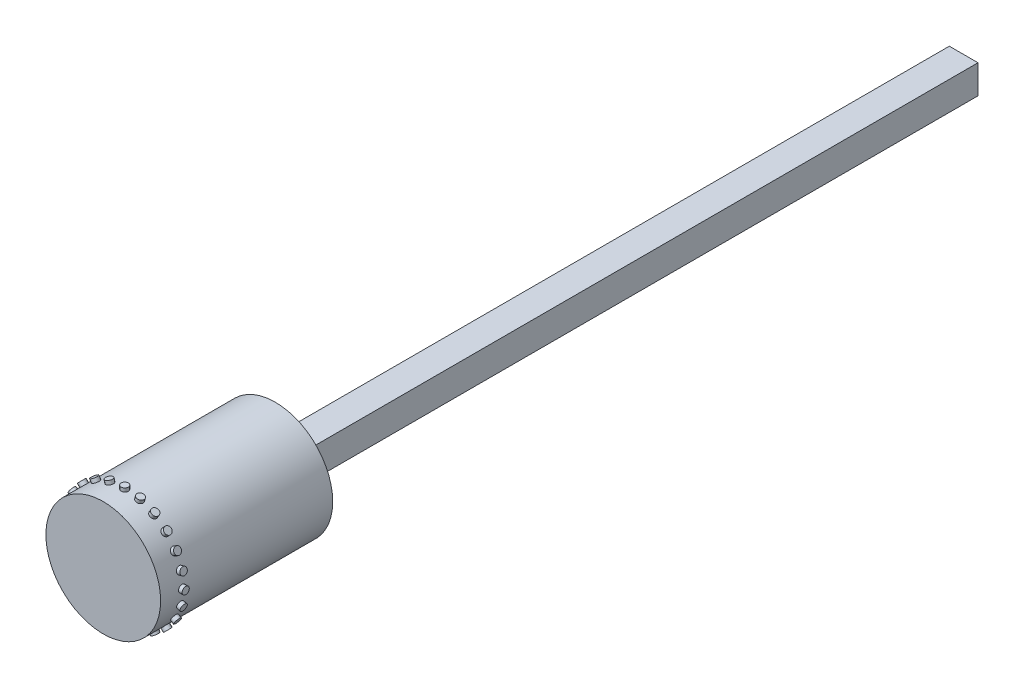
SolidWorks part; units mm, degrees
ref_plane "Front Plane" through (0, 0, 0) normal (0, 0, 1) x (1, 0, 0)
ref_plane "Top Plane" through (0, 0, 0) normal (0, 1, 0) x (1, 0, 0)
ref_plane "Right Plane" through (0, 0, 0) normal (1, 0, 0) x (0, 0, -1)
sketch "Sketch1" plane through (0, 0, 0) normal (0, 0, 1) x (1, 0, 0)
  circle A0 centre (0, 0) radius 50.8
  dimension "D1" = 101.6
extrude "Boss-Extrude1" add sketch "Sketch1" along normal blind 152.4
sketch "Sketch2" plane through (0, 0, 0) normal (0, 0, -1) x (-1, 0, 0)
  line L1 (-12.7, -12.7) -> (12.7, -12.7)
  line L2 (-12.7, -12.7) -> (-12.7, 12.7)
  line L3 (-12.7, 12.7) -> (12.7, 12.7)
  line L4 (12.7, -12.7) -> (12.7, 12.7)
  line L5 (-12.7, -12.7) -> (12.7, 12.7) construction
  line L6 (-12.7, 12.7) -> (12.7, -12.7) construction
  point P0 (0, 0)
  dimension "D1" = 25.4
  dimension "D2" = 25.4
extrude "Boss-Extrude2" add sketch "Sketch2" along normal blind 609.6
sketch "Sketch3" plane through (0, 0, 0) normal (0, 1, 0) x (1, 0, 0)
  line L0 (-50.8, -152.4) -> (50.8, -152.4) construction
  circle A0 centre (0, -133.35) radius 3.175
  dimension "D1" = 6.35
  dimension "D2" = 19.05
extrude "Boss-Extrude3" add sketch "Sketch3" along normal blind 53.975 contours A0
pattern_circular "CirPattern1" count 24 every 15 about axis through (0, 0, 0) along (0, 0, 1) of "Boss-Extrude3"
